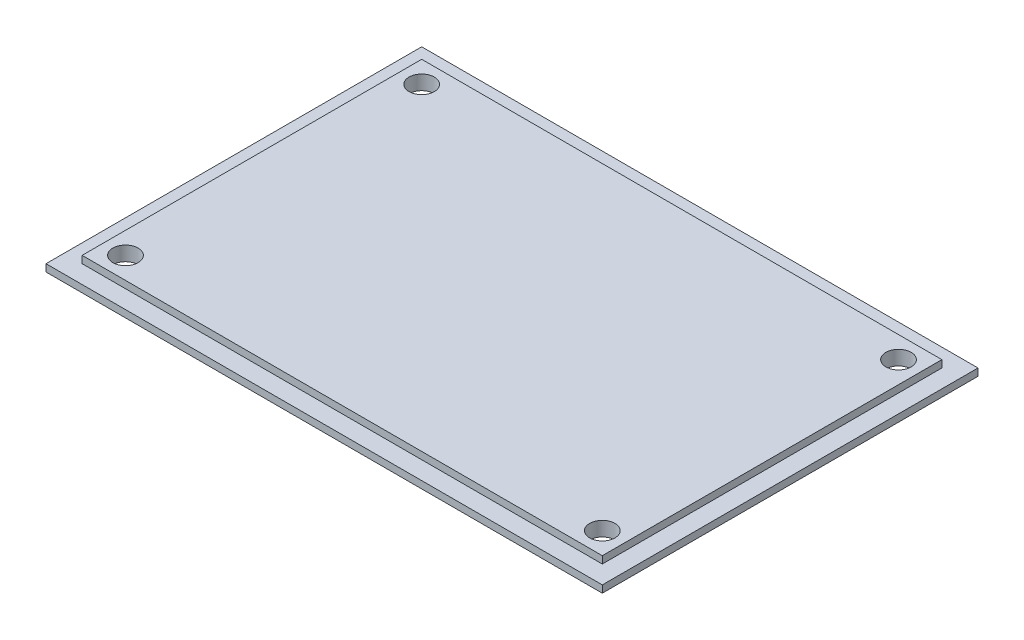
SolidWorks part; units mm, degrees
ref_plane "Front Plane" through (0, 0, 0) normal (0, 0, 1) x (1, 0, 0)
ref_plane "Top Plane" through (0, 0, 0) normal (0, 1, 0) x (1, 0, 0)
ref_plane "Right Plane" through (0, 0, 0) normal (1, 0, 0) x (0, 0, -1)
sketch "Sketch1" plane through (0, 0, 0) normal (0, 1, 0) x (1, 0, 0)
  line L1 (-38.5, 26) -> (38.5, 26)
  line L2 (-38.5, 26) -> (-38.5, -26)
  line L3 (-38.5, -26) -> (38.5, -26)
  line L4 (38.5, 26) -> (38.5, -26)
  line L5 (-38.5, 26) -> (38.5, -26) construction
  line L6 (-38.5, -26) -> (38.5, 26) construction
  point P0 (0, 0)
  dimension "D1" = 77
  dimension "D2" = 52
extrude "Boss-Extrude1" add sketch "Sketch1" along normal blind 1
sketch "Sketch2" plane through (0, 1, 0) normal (0, 1, 0) x (1, 0, 0)
  line L0 (38.5, 26) -> (-38.5, 26) construction
  line L1 (-36, 23.5) -> (36, 23.5)
  line L2 (-36, 23.5) -> (-36, -23.5)
  line L3 (-36, -23.5) -> (36, -23.5)
  line L4 (36, 23.5) -> (36, -23.5)
  line L5 (-36, 23.5) -> (36, -23.5) construction
  line L6 (-36, -23.5) -> (36, 23.5) construction
  line L7 (38.5, -26) -> (38.5, 26) construction
  point P0 (0, 0)
  dimension "D1" = 2.5
  dimension "D2" = 2.5
extrude "Boss-Extrude2" add sketch "Sketch2" along normal blind 1
sketch "Sketch3" plane through (0, 2, 0) normal (0, 1, 0) x (1, 0, 0)
  line L0 (36, 23.5) -> (-36, 23.5) construction
  line L1 (-36, 23.5) -> (-36, -23.5) construction
  line L2 (36, 23.5) -> (-36, 23.5) construction
  line L3 (36, -23.5) -> (36, 23.5) construction
  line L4 (-36, -23.5) -> (36, -23.5) construction
  line L5 (36, -23.5) -> (36, 23.5) construction
  circle A0 centre (-33, 20.5) radius 1.75
  circle A1 centre (33, 20.5) radius 1.75
  circle A2 centre (33, -20.5) radius 1.75
  circle A3 centre (-33, -20.5) radius 1.75
  dimension "D1" = 3.5
  dimension "D2" = 3.5
  dimension "D3" = 3.5
  dimension "D4" = 3.5
  dimension "D5" = 3
  dimension "D6" = 3
  dimension "D7" = 3
  dimension "D8" = 3
  dimension "D9" = 3
  dimension "D10" = 3
  dimension "D11" = 3
  dimension "D12" = 3
extrude "Cut-Extrude1" cut sketch "Sketch3" against normal blind 11
sketch "Sketch4" plane through (0, 0, 0) normal (0, -1, 0) x (1, 0, 0)
  text T0 "<b>Servo Board</b>" font "Century Gothic" height in points 24
  point P1 (-20.6316, 5.5947)
  point P2 (-24.0465, 6.1406)
  point P3 (0, 0)
  point P4 (-26.2402, 5.8063)
  point P5 (-24.7501, 5.7964)
extrude "Cut-Extrude2" cut sketch "Sketch4" against normal blind 0.4
